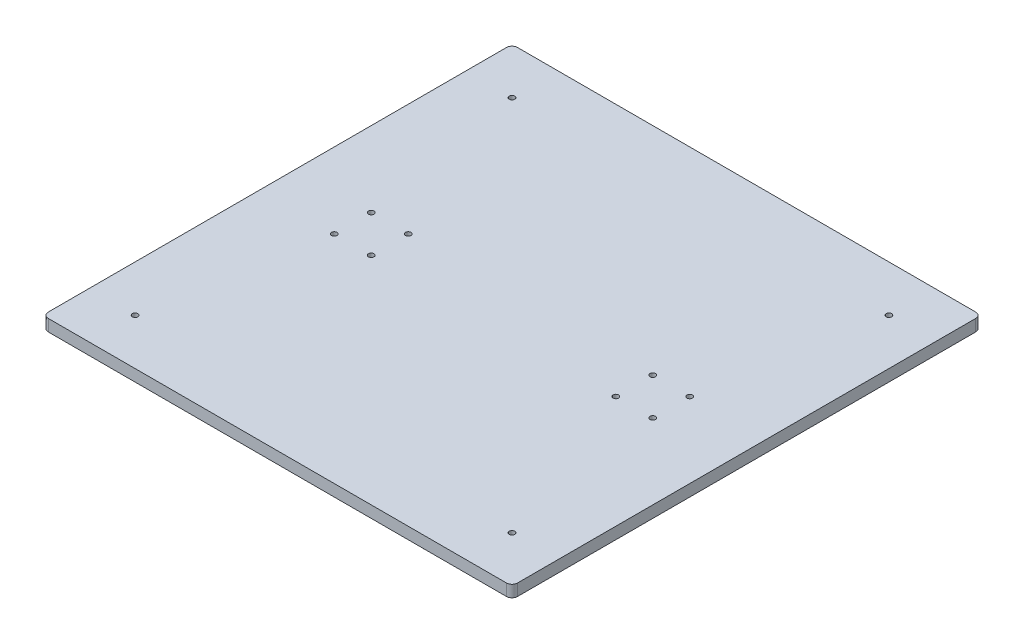
SolidWorks part; units mm, degrees
ref_plane "Front Plane" through (0, 0, 0) normal (0, 0, 1) x (1, 0, 0)
ref_plane "Top Plane" through (0, 0, 0) normal (0, 1, 0) x (1, 0, 0)
ref_plane "Right Plane" through (0, 0, 0) normal (1, 0, 0) x (0, 0, -1)
sketch "Sketch1" plane through (0, 0, 0) normal (0, 1, 0) x (1, 0, 0)
  line L1 (-124, 127) -> (124, 127)
  line L2 (-127, 124) -> (-127, -124)
  line L3 (-124, -127) -> (124, -127)
  line L4 (127, 124) -> (127, -124)
  line L5 (-127, 127) -> (127, -127) construction
  line L6 (-127, -127) -> (127, 127) construction
  arc A0 (-127, -124) -> (-124, -127) centre (-124, -124) ccw
  arc A1 (124, -127) -> (127, -124) centre (124, -124) ccw
  arc A2 (124, 127) -> (127, 124) centre (124, 124) cw
  arc A3 (-124, 127) -> (-127, 124) centre (-124, 124) ccw
  point P0 (0, 0)
  dimension "D3" = 3
  dimension "D1" = 254
  dimension "D2" = 254
extrude "Boss-Extrude1" add sketch "Sketch1" along normal blind 6.35
hole_wizard "Ø3.0mm Dowel Hole1" positions "Sketch3" profile "Sketch4" hole size "Ø3.0" standard "ANSI Metric" end condition through all
sketch "Sketch3" plane through (0, 6.35, 0) normal (0, 1, 0) x (1, 0, 0)
  line L2 (0, 135.2129) -> (0, -150.5896) construction
  line L4 (-149.8244, 0) -> (231.3195, 0) construction
  point P0 (-102, 102)
  point P16 (-102, -102)
  point P17 (102, -102)
  point P18 (102, 102)
  dimension "D1" = 102
  dimension "D2" = 102
sketch "Sketch4" plane through (-102, 6.35, -102) normal (1, 0, 0) x (0, 0, 1)
  line L0 (0, 0) -> (0, 6.35)
  line L1 (0, 6.35) -> (1.5, 6.35)
  line L2 (1.5, 6.35) -> (1.5, 0)
  line L5 (1.5, 0) -> (0, 0)
  line L11 (0, -6.35) -> (0, 107.95) construction
  dimension "Thru Hole Dia." = 3
  dimension "Thru Hole Depth" = 6.35
hole_wizard "Ø3.0mm Dowel Hole2" positions "Sketch5" profile "Sketch6" hole size "Ø3.0" standard "ANSI Metric" end condition through all
sketch "Sketch5" plane through (0, 6.35, 0) normal (0, 1, 0) x (1, 0, 0)
  line L0 (-206.9136, 0) -> (183.7915, 0) construction
  line L2 (0, -163.5461) -> (0, 208.6725) construction
  line L3 (-76.2, 137.4211) -> (-76.2, -151.1835) construction
  point P44 (-66.2, 10)
  point P46 (-66.2, -10)
  point P48 (-86.2, -10.0256)
  point P50 (-86.2, 9.9744)
  point P54 (86.2, 9.9744)
  point P55 (86.2, -10.0256)
  point P56 (66.2, -10)
  point P57 (66.2, 10)
  dimension "D1" = 20
  dimension "D2" = 20
  dimension "D3" = 20
  dimension "D4" = 20
  dimension "D5" = 10
  dimension "D6" = 76.2
  dimension "D7" = 10
sketch "Sketch6" plane through (66.2, 6.35, -10) normal (1, 0, 0) x (0, 0, 1)
  line L0 (0, 0) -> (0, 6.35)
  line L1 (0, 6.35) -> (1.5, 6.35)
  line L2 (1.5, 6.35) -> (1.5, 0)
  line L5 (1.5, 0) -> (0, 0)
  line L11 (0, -6.35) -> (0, 107.95) construction
  dimension "Thru Hole Dia." = 3
  dimension "Thru Hole Depth" = 6.35
